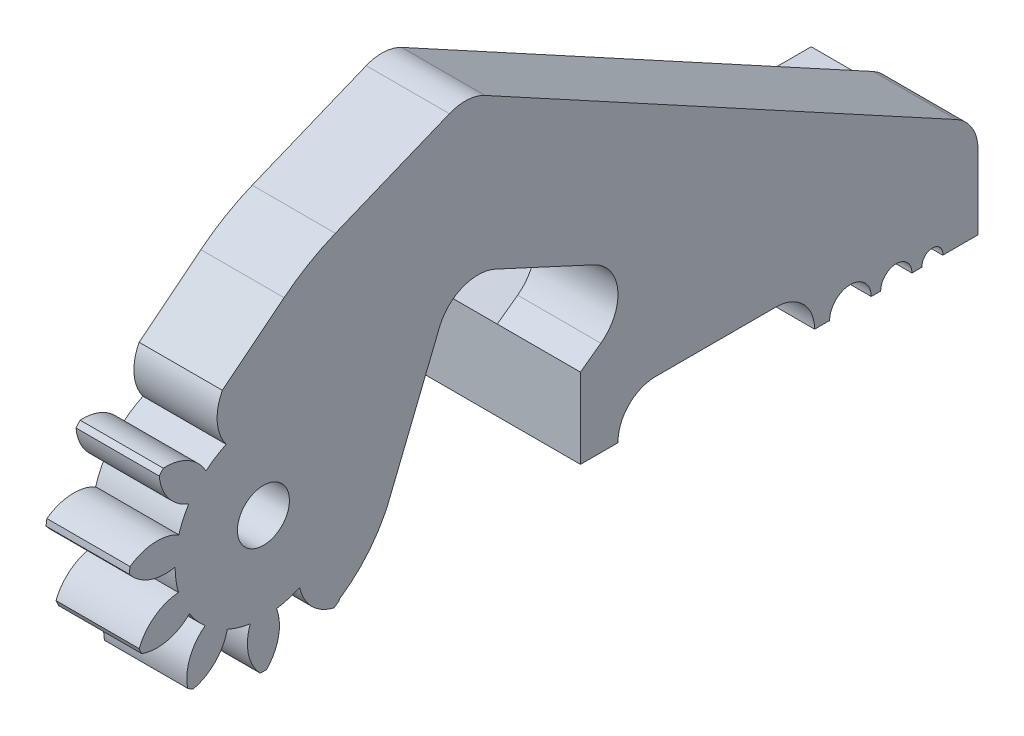
SolidWorks part; units mm, degrees
ref_plane "Plane1" through (0, 0, 0) normal (0, 0, 1) x (1, 0, 0)
ref_plane "Plane2" through (0, 0, 0) normal (0, 1, 0) x (1, 0, 0)
ref_plane "Plane3" through (0, 0, 0) normal (1, 0, 0) x (0, 0, -1)
sketch "HoldingSke" plane through (0, 0, 0) normal (0, 1, 0) x (1, 0, 0)
  line L0 (0, 0) -> (0.9816, -0.1908)
  line L1 (-15, 0) -> (100, 0) construction
  line L2 (0, 0) -> (-2.1039, 2.3779)
  line L3 (0, 0) -> (-11.863, 4.5341)
  line L4 (0, 0) -> (8.4773, 1.6478)
  line L5 (0, 0) -> (-46.8476, -17.4728)
  line L6 (0, 0) -> (-3.3159, -2.2372)
  line L7 (-2.1039, 2.3779) -> (8.6586, 51.2059)
  line L8 (-76.2, 54.61) -> (-75.9, 54.61)
  line L9 (-71.009, 38.7566) -> (-53.1078, 45.2721)
  line L10 (-76.2, 71.12) -> (104.1128, 71.12)
  line L11 (0, 0) -> (-4, 0)
  line L12 (-76.2, 101.6) -> (-76.162, 101.6)
  line L13 (24.9733, 27.94) -> (52.9518, 28.4284)
  line L14 (24.9733, 27.94) -> (24.9743, 27.94)
  line L15 (24.9733, 27.94) -> (100.4006, 29.5858)
  line L16 (-63.627, -1) -> (-12.827, -1)
  circle A0 centre (0, 0) radius 1
  circle A1 centre (0, 0) radius 4.249
  circle A2 centre (0, 0) radius 37.5
  circle A3 centre (0, 0) radius 1
  dimension "MHD" = 8.498
  dimension "Hub_dia" = 75
  dimension "Bore" = 2
  dimension "MBD" = 2
  dimension "Num_teeth" = 11
  dimension "Pitch" = 1
  dimension "Overall_len" = 50
  dimension "Show_teeth" = 11
  dimension "Thickness" = 4
  dimension "OAL" = 50.0001
  dimension "T_dim" = 0.3
  dimension "Ap" = 20
  dimension "H" = 19.05
  dimension "Pitch_radius" = 180.3128
  dimension "Width" = 4
  dimension "Backlash" = 0.038
  dimension "Addendum_fac" = 1
  dimension "Dedendum_fac" = 1.25
  dimension "Clearance_fac" = 0.25
  dimension "Dedendum_add" = 0.001
  dimension "Module" = 1
sketch "BasProSke" plane through (0, 0, 0) normal (0, 1, 0) x (1, 0, 0)
  line L0 (-10, 0) -> (60, 0) construction
  line L1 (0, 0) -> (0, 6.5)
  line L2 (0, 0) -> (4, 0)
  line L3 (4, 0) -> (4, 6.5)
  line L4 (4, 6.5) -> (0, 6.5)
  dimension "Thickness" = 4
  dimension "Diameter" = 13
revolve "Base-Revolve" add sketch "BasProSke" angle 360 about L0
sketch "TooCutSke" plane through (0, 0, 0) normal (1, 0, 0) x (0, 0, -1)
  line L1 (0, 0) -> (0, 107) construction
  line L2 (0, 0) -> (-0.8491, 5.4341) construction
  line L3 (0, 0) -> (-3.0727, 10.4645) construction
  line L4 (-0.8491, 5.4341) -> (-1.5363, 5.2323) construction
  arc A0 (0.576, 4.2098) -> (-0.576, 4.2098) centre (0, 0) ccw
  arc A1 (1.7187, 6.295) -> (-1.7187, 6.295) centre (0, 0) ccw
  circle A2 centre (0, 0) radius 5.5 construction
  circle A3 centre (0, 0) radius 5.1683 construction
  arc A4 (-0.576, 4.2098) -> (-1.7187, 6.295) centre (-2.7707, 4.3629) ccw
  arc A5 (1.7187, 6.295) -> (0.576, 4.2098) centre (2.7707, 4.3629) ccw
  dimension "Root_dia" = 8.498
  dimension "Overcut_dia" = 13.0508
  dimension "Pitch_dia" = 11
  dimension "Base_dia" = 10.3366
  dimension "Flank_rad" = 2.2
  dimension "Half_ang" = 16.364
  dimension "Half_CT" = 0.7162
extrude "ToothCut" cut sketch "TooCutSke" along normal through all
fillet "Breaks" [suppressed] radius 0.02
fillet "RootFillets" [suppressed] radius 0.251
pattern_circular "TeethCuts" count 11 every 32.727 about axis through (-10, 0, 0) along (1, 0, 0) of "ToothCut", "RootFillets", "Breaks"
sketch "HubNeaOneSke" plane through (0, 0, 0) normal (-1, 0, 0) x (0, 0, 1)
  circle A0 centre (0, 0) radius 4.249
  dimension "Diameter" = 8.498
extrude "HubNearOne" [suppressed] add sketch "HubNeaOneSke" along normal blind 46.0001
sketch "HubNeaBotSke" plane through (0, 0, 0) normal (-1, 0, 0) x (0, 0, 1)
  circle A0 centre (0, 0) radius 4.249
  dimension "Diameter" = 8.498
extrude "HubNearBoth" [suppressed] add sketch "HubNeaBotSke" along normal blind 23
ref_plane "FarPln" through (4, 0, 0) normal (1, 0, 0) x (0, 0, -1)
sketch "HubFarSke" plane through (4, 0, 0) normal (1, 0, 0) x (0, 0, -1)
  circle A0 centre (0, 0) radius 4.249
  dimension "Diameter" = 8.498
extrude "HubFar" [suppressed] add sketch "HubFarSke" along normal blind 23
sketch "BorSke" plane through (0, 0, 0) normal (1, 0, 0) x (0, 0, -1)
  circle A0 centre (0, 0) radius 1.25
  dimension "Diameter" = 2.5
extrude "Bore" cut sketch "BorSke" along normal mid plane 125.0001
sketch "KeySke" plane through (0, 0, 0) normal (1, 0, 0) x (0, 0, -1)
  line L0 (-0.4, 0) -> (-0.4, 1.3)
  line L1 (-0.4, 1.3) -> (0.4, 1.3)
  line L2 (0.4, 1.3) -> (0.4, 0)
  line L3 (0, 0) -> (0, 34) construction
  line L4 (-0.4, 0) -> (0.4, 0)
  dimension "Offset" = 1.3
  dimension "Width" = 0.8
extrude "Keyway" [suppressed] cut sketch "KeySke" along normal mid plane 100.0001
pattern_circular "Keyway2" [suppressed] count 2 every 90 about axis through (-10, 0, 0) along (1, 0, 0)
sketch "Çizim1" plane through (4, 0, 0) normal (1, 0, 0) x (0, 0, -1)
  line L12 (29.2198, -5.5) -> (29.676, -5.5) construction
  line L13 (18.8518, -3.6472) -> (24.6452, -3.6472) construction
  line L15 (26.498, -5.5) -> (27.2198, -5.5) construction
  line L16 (31.1757, -5.5) -> (31.6654, -5.5) construction
  line L17 (32.6605, -5.5) -> (34.0959, -5.5) construction
  line L18 (2.7608, -3.2299) -> (1.236, 1.2903)
  line L21 (5.9627, -2.5878) -> (8.493, 3.6732)
  line L22 (8.9406, 12.2518) -> (2.1208, 9.4681)
  line L23 (11.1571, 4.6719) -> (15.8839, 2.4888)
  line L24 (16.2215, -0.9445) -> (15.2413, -1.6572)
  line L25 (15.2413, -1.6572) -> (15.2413, -5.5)
  line L26 (15.2413, -5.5) -> (17.0494, -5.5)
  line L27 (18.8518, -3.6472) -> (24.6452, -3.6472)
  line L28 (26.498, -5.5) -> (27.2198, -5.5)
  line L29 (29.2198, -5.5) -> (29.676, -5.5)
  line L30 (31.1757, -5.5) -> (31.6654, -5.5)
  line L31 (32.6605, -5.5) -> (34.3536, -5.5)
  line L32 (34.3536, -5.5) -> (34.3536, -1.9306)
  line L33 (33.3097, -0.1739) -> (10.6524, 12.1568)
  line L37 (1.236, 1.2903) -> (-1.739, 3.8768)
  line L38 (2.1208, 9.4681) -> (-1.9747, 6.1928)
  arc A0 (3.6395, -5.3856) -> (2.8043, -3.1922) centre (1.4828, -4.951) ccw construction
  arc A1 (18.8518, -3.6472) -> (17.0494, -5.5) centre (18.8518, -5.4503) ccw construction
  arc A2 (26.498, -5.5) -> (24.6452, -3.6472) centre (24.6452, -5.5) ccw construction
  arc A3 (29.2198, -5.5) -> (27.2198, -5.5) centre (28.2198, -5.5) ccw construction
  arc A4 (31.1757, -5.5) -> (29.676, -5.5) centre (30.4259, -5.4861) ccw construction
  arc A5 (32.6605, -5.5) -> (31.6654, -5.5) centre (32.163, -5.4503) ccw construction
  arc A6 (5.8487, -2.836) -> (5.9734, -2.563) centre (0, 0) ccw construction
  arc A33 (2.7608, -3.2299) -> (3.6525, -5.3148) centre (4.9401, -3.5309) ccw
  arc A34 (3.6525, -5.3148) -> (5.9627, -2.5878) centre (0.0391, 0.0883) ccw
  arc A35 (11.1571, 4.6719) -> (8.493, 3.6732) centre (10.3185, 2.8562) ccw
  arc A36 (16.2215, -0.9445) -> (15.8839, 2.4888) centre (15.0453, 0.6731) ccw
  arc A37 (18.8518, -3.6472) -> (17.0494, -5.5) centre (18.8518, -5.4503) ccw
  arc A38 (26.498, -5.5) -> (24.6452, -3.6472) centre (24.6452, -5.5) ccw
  arc A39 (29.2198, -5.5) -> (27.2198, -5.5) centre (28.2198, -5.5) ccw
  arc A40 (31.1757, -5.5) -> (29.676, -5.5) centre (30.4259, -5.4861) ccw
  arc A41 (32.6605, -5.5) -> (31.6654, -5.5) centre (32.163, -5.4503) ccw
  arc A42 (34.3536, -1.9306) -> (33.3097, -0.1739) centre (32.3536, -1.9306) ccw
  arc A43 (10.6524, 12.1568) -> (8.9406, 12.2518) centre (9.6964, 10.4001) ccw
  arc A45 (-1.9747, 6.1928) -> (-1.739, 3.8768) centre (0.0004, 5.2239) ccw
  arc A49 (-1.9747, 6.1928) -> (-1.7914, 3.8529) centre (-0.0279, 5.1682) ccw construction
  arc A50 (-1.6868, 6.2773) -> (-1.9747, 6.1928) centre (0, 0) ccw construction
  point P9 (21.7485, -5.4503)
  dimension "D1" = 2
  dimension "D2" = 1.5
extrude "Yükseklik-Ekstrüzyon1" add sketch "Çizim1" against normal up to surface (4 mm away) up to face at (0, 0, -1.25)
sketch "Çizim2" plane through (0, 0, 0) normal (-1, 0, 0) x (0, 0, 1)
  line L0 (-34.3536, -1.9306) -> (-34.3536, -5.5) construction
  line L1 (-34.3536, -5.5) -> (-32.6605, -5.5) construction
  line L2 (-31.6654, -5.5) -> (-31.1757, -5.5) construction
  line L3 (-29.676, -5.5) -> (-29.2198, -5.5) construction
  line L4 (-27.2198, -5.5) -> (-26.498, -5.5) construction
  line L5 (-24.6452, -3.6472) -> (-18.8518, -3.6472) construction
  line L6 (-17.0494, -5.5) -> (-15.2413, -5.5) construction
  line L7 (-15.2413, -5.5) -> (-15.2413, -1.6572) construction
  line L8 (-34.3536, -1.9306) -> (-34.3536, -5.5)
  line L9 (-34.3536, -5.5) -> (-32.6605, -5.5)
  line L10 (-31.6654, -5.5) -> (-31.1757, -5.5)
  line L11 (-29.676, -5.5) -> (-29.2198, -5.5)
  line L12 (-27.2198, -5.5) -> (-26.498, -5.5)
  line L13 (-24.6452, -3.6472) -> (-18.8518, -3.6472)
  line L14 (-17.0494, -5.5) -> (-15.2413, -5.5)
  line L15 (-15.2413, -5.5) -> (-15.2413, -1.6572)
  line L16 (-15.2413, -1.6572) -> (-34.3349, -1.6572)
  arc A0 (-33.3097, -0.1739) -> (-34.3536, -1.9306) centre (-32.3536, -1.9306) ccw construction
  arc A1 (-31.6654, -5.5) -> (-32.6605, -5.5) centre (-32.163, -5.4503) ccw construction
  arc A2 (-29.676, -5.5) -> (-31.1757, -5.5) centre (-30.4259, -5.4861) ccw construction
  arc A3 (-27.2198, -5.5) -> (-29.2198, -5.5) centre (-28.2198, -5.5) ccw construction
  arc A4 (-24.6452, -3.6472) -> (-26.498, -5.5) centre (-24.6452, -5.5) ccw construction
  arc A5 (-17.0494, -5.5) -> (-18.8518, -3.6472) centre (-18.8518, -5.4503) ccw construction
  arc A6 (-34.3349, -1.6572) -> (-34.3536, -1.9306) centre (-32.3536, -1.9306) ccw
  arc A7 (-31.6654, -5.5) -> (-32.6605, -5.5) centre (-32.163, -5.4503) ccw
  arc A8 (-29.676, -5.5) -> (-31.1757, -5.5) centre (-30.4259, -5.4861) ccw
  arc A9 (-27.2198, -5.5) -> (-29.2198, -5.5) centre (-28.2198, -5.5) ccw
  arc A10 (-24.6452, -3.6472) -> (-26.498, -5.5) centre (-24.6452, -5.5) ccw
  arc A11 (-17.0494, -5.5) -> (-18.8518, -3.6472) centre (-18.8518, -5.4503) ccw
extrude "Yükseklik-Ekstrüzyon2" add sketch "Çizim2" along normal blind 4
fillet "Radyus1" radius 10 1 edges at (2, 9.4681, -2.1208)
equation "' \"Module@HoldingSke\" = 6.35"
equation "' \"Num_teeth@HoldingSke\" = 12"
equation "' \"Ap@HoldingSke\" =  20"
equation "' \"Ap@HoldingSke\" = 20"
equation "' \"Width@HoldingSke\" = 0.5 * 25.4"
equation "' \"Hub_dia@HoldingSke\"= 1 * 25.4"
equation "' \"Hub_dia@HoldingSke\" = 1 * 25.4"
equation "' \"Overall_len@HoldingSke\" = 1.0 * 25.4"
equation "' \"Bore@HoldingSke\" = 0.75 * 25.4"
equation "' \"T_dim@HoldingSke\" = 0.1 * 25.4"
equation "' \"Width@KeySke\" = 0.25 * 25.4"
equation "' \"Show_teeth@HoldingSke\" = 13"
equation "' \"Backlash@HoldingSke\" = 0.009 * 25.4"
equation "' \"Addendum_fac@HoldingSke\" = 1.0"
equation "' \"Dedendum_fac@HoldingSke\" = 1.25"
equation "' \"Dedendum_add@HoldingSke\" = 0.00005 * 25.4"
equation "' \"Clearance_fac@HoldingSke\" = 0.25"
equation "\"Pitch@HoldingSke\" = 1 / \"Module@HoldingSke\""
equation "\"Overcut_dia@TooCutSke\" = (\"Num_teeth@HoldingSke\" + 2 * \"Addendum_fac@HoldingSke\") / \"Pitch@HoldingSke\" + 0.002 * 25.4"
equation "\"Pitch_dia@TooCutSke\" = \"Num_teeth@HoldingSke\" / \"Pitch@HoldingSke\""
equation "\"Base_dia@TooCutSke\" = \"Num_teeth@HoldingSke\" / \"Pitch@HoldingSke\" * cos((\"Ap@HoldingSke\"  * 3.14159265 / 180))"
equation "\"Root_dia@TooCutSke\" = (\"Num_teeth@HoldingSke\" + 2) / \"Pitch@HoldingSke\" - 2 * (\"Addendum_fac@HoldingSke\" + \"Dedendum_fac@HoldingSke\") / \"Pitch@HoldingSke\" - \"Dedendum_add@HoldingSke\" * 2"
equation "\"Half_ang@TooCutSke\" = 180 / \"Num_teeth@HoldingSke\""
equation "\"Half_CT@TooCutSke\" = \"Num_teeth@HoldingSke\" / \"Pitch@HoldingSke\" * sin((3.14159265 / 2 / \"Num_teeth@HoldingSke\")) / 2 - 7 * \"Backlash@HoldingSke\" / 4"
equation "\"Flank_rad@TooCutSke\" = \"Num_teeth@HoldingSke\" / \"Pitch@HoldingSke\" / 5"
equation "\"Radius@RootFillets\" = \"Clearance_fac@HoldingSke\" / \"Pitch@HoldingSke\" + \"Dedendum_add@HoldingSke\""
equation "\"Break_rad@Breaks\" = 0.02 / \"Pitch@HoldingSke\""
equation "\"Thickness@HoldingSke\" = \"Width@HoldingSke\""
equation "\"OAL@HoldingSke\" = \"Thickness@HoldingSke\""
equation "\"MHD@HoldingSke\" = (\"Num_teeth@HoldingSke\" + 2) / \"Pitch@HoldingSke\" - 2 * (\"Addendum_fac@HoldingSke\" + \"Dedendum_fac@HoldingSke\")  / \"Pitch@HoldingSke\" - \"Dedendum_add@HoldingSke\" * 2"
equation "\"MBD@HoldingSke\" = (\"Num_teeth@HoldingSke\" + 2) / \"Pitch@HoldingSke\" - 2 * (\"Addendum_fac@HoldingSke\" + \"Dedendum_fac@HoldingSke\")  / \"Pitch@HoldingSke\" - \"Dedendum_add@HoldingSke\" * 2 - 0.002 * 25.4"
equation "\"MHD@HoldingSke\" = ((sgn( \"MHD@HoldingSke\" - \"Hub_dia@HoldingSke\" )-1)*( \"MHD@HoldingSke\" - \"Hub_dia@HoldingSke\" ))/-2+ \"Hub_dia@HoldingSke\""
equation "\"MBD@HoldingSke\" = ((sgn( \"MBD@HoldingSke\" - \"Bore@HoldingSke\" )-1)*( \"MBD@HoldingSke\" - \"Bore@HoldingSke\" ))/-2+ \"Bore@HoldingSke\""
equation "\"OAL@HoldingSke\" = ((sgn( \"OAL@HoldingSke\" - \"Overall_len@HoldingSke\" )+1)*( \"OAL@HoldingSke\" - \"Overall_len@HoldingSke\" ))/2 + \"Overall_len@HoldingSke\" + 0.000002 * 25.4"
equation "\"Num_teeth@TeethCuts\" = int( \"Show_teeth@HoldingSke\" ) + 1"
equation "\"Num_teeth@TeethCuts\" = ((sgn( \"Num_teeth@TeethCuts\" - \"Num_teeth@HoldingSke\" )-1)*( \"Num_teeth@TeethCuts\" - \"Num_teeth@HoldingSke\" ))/-2+ \"Num_teeth@HoldingSke\""
equation "\"Num_teeth@TeethCuts\" = ((sgn( \"Num_teeth@TeethCuts\" - 2.0)+1)*( \"Num_teeth@TeethCuts\" - 2.0))/2 +2.0"
equation "\"Angle@TeethCuts\" = 360.0 / \"Num_teeth@HoldingSke\""
equation "\"Diameter@BasProSke\" = (\"Num_teeth@HoldingSke\" + 2 * \"Addendum_fac@HoldingSke\") / \"Pitch@HoldingSke\""
equation "\"Thickness@BasProSke\"  = \"Thickness@HoldingSke\""
equation "' \"Fillet_rad@BasProSke\" =  \"Thickness@HoldingSke\" * 0.05"
equation "' \"Fillet_rad@BasProSke\" = \"Thickness@HoldingSke\" * 0.05"
equation "\"MHD@HoldingSke\" = ((sgn( \"MHD@HoldingSke\" - \"Root_dia@TooCutSke\" )-1)*( \"MHD@HoldingSke\" - \"Root_dia@TooCutSke\" ))/-2+ \"Root_dia@TooCutSke\""
equation "\"Diameter@HubNeaOneSke\" = \"MHD@HoldingSke\""
equation "\"Length@HubNearOne\" = \"OAL@HoldingSke\" - \"Thickness@BasProSke\""
equation "\"Diameter@HubNeaBotSke\" = \"MHD@HoldingSke\""
equation "\"Length@HubNearBoth\" = ( \"OAL@HoldingSke\" - \"Thickness@BasProSke\" ) / 2.0"
equation "\"Thickness@FarPln\" = \"Thickness@BasProSke\""
equation "\"Diameter@HubFarSke\" = \"MHD@HoldingSke\""
equation "\"Length@HubFar\" = ( \"OAL@HoldingSke\" - \"Thickness@BasProSke\" ) / 2.0"
equation "\"D1@Bore\"=\"OAL@HoldingSke\" * 2.5"
equation "\"D1@Keyway\" = \"OAL@HoldingSke\" * 2.0"
equation "\"Offset@KeySke\" = \"T_dim@HoldingSke\" + \"MBD@HoldingSke\" / 2.0"
